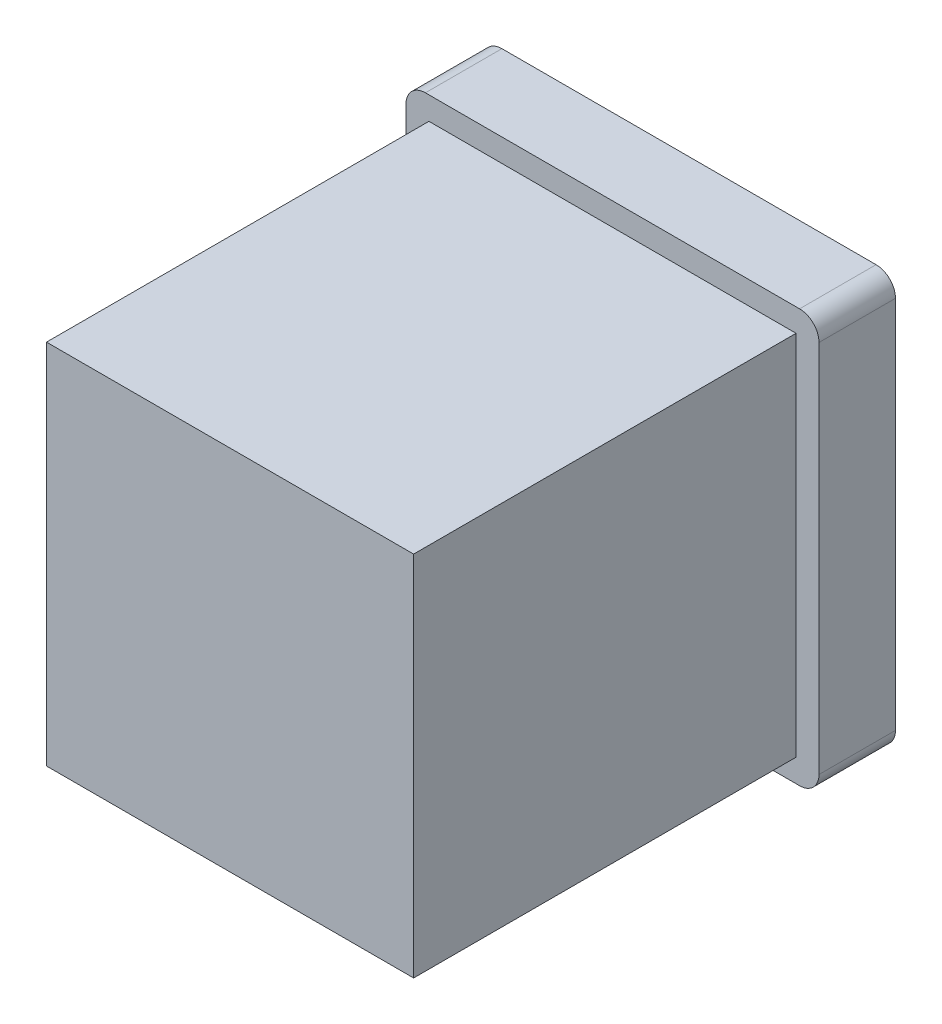
SolidWorks part; units mm, degrees
ref_plane "Front Plane" through (0, 0, 0) normal (0, 0, 1) x (1, 0, 0)
ref_plane "Top Plane" through (0, 0, 0) normal (0, 1, 0) x (1, 0, 0)
ref_plane "Right Plane" through (0, 0, 0) normal (1, 0, 0) x (0, 0, -1)
sketch "Sketch1" plane through (0, 0, 0) normal (0, 0, 1) x (1, 0, 0)
  line L1 (0, 0) -> (27, 0)
  line L2 (0, 0) -> (0, 27)
  line L3 (0, 27) -> (27, 27)
  line L4 (27, 0) -> (27, 27)
  dimension "D1" = 27
  dimension "D2" = 27
extrude "Boss-Extrude1" add sketch "Sketch1" along normal blind 5
sketch "Sketch2" plane through (0, 0, 5) normal (0, 0, 1) x (1, 0, 0)
  line L0 (0, 27) -> (0, 0) construction
  line L1 (1.5, 25.5) -> (25.5, 25.5)
  line L2 (1.5, 25.5) -> (1.5, 1.5)
  line L3 (1.5, 1.5) -> (25.5, 1.5)
  line L4 (25.5, 25.5) -> (25.5, 1.5)
  line L5 (27, 27) -> (0, 27) construction
  point P4 (1.5, 13.5)
  point P7 (0, 13.5)
  point P8 (13.5, 25.5)
  point P11 (13.5, 27)
  dimension "D1" = 0
  dimension "D2" = 0
  dimension "D3" = 24
  dimension "D4" = 24
extrude "Boss-Extrude2" add sketch "Sketch2" along normal blind 25
fillet "Fillet1" radius 1.27 4 edges at (0, 0, 2.5) (27, 0, 2.5) (0, 27, 2.5) (27, 27, 2.5)
sketch "Sketch3" plane through (0, 0, 0) normal (0, 0, -1) x (-1, 0, 0)
  line L0 (-27, 1.27) -> (-27, 25.73) construction
  line L1 (-20.65, 23.19) -> (-18.11, 23.19)
  line L2 (-20.65, 23.19) -> (-20.65, 15.57)
  line L3 (-20.65, 15.57) -> (-18.11, 15.57)
  line L4 (-18.11, 23.19) -> (-18.11, 15.57)
  line L5 (-25.73, 27) -> (-1.27, 27) construction
  line L6 (-8.89, 23.19) -> (-6.35, 23.19)
  line L7 (-8.89, 23.19) -> (-8.89, 15.57)
  line L8 (-8.89, 15.57) -> (-6.35, 15.57)
  line L9 (-6.35, 23.19) -> (-6.35, 15.57)
  line L10 (0, 25.73) -> (0, 1.27) construction
  line L11 (-13.625, 1.4094) -> (-13.625, 7.8295) construction
  line L12 (-16.165, 5.08) -> (-16.165, 8.636)
  line L13 (-11.085, 5.08) -> (-11.085, 8.636)
  line L14 (-16.165, 5.08) -> (-11.085, 5.08)
  line L15 (-1.27, 0) -> (-25.73, 0) construction
  arc A1 (-11.085, 8.636) -> (-16.165, 8.636) centre (-13.625, 7.8295) ccw
  point P16 (-13.5, 5.1417)
  dimension "D10" = 2.665
  dimension "D1" = 2.54
  dimension "D2" = 7.62
  dimension "D3" = 6.35
  dimension "D4" = 2.54
  dimension "D5" = 7.62
  dimension "D6" = 3.81
  dimension "D7" = 6.35
  dimension "D8" = 3.81
  dimension "D9" = 5.08
  dimension "D11" = 3.556
  dimension "D12" = 11.085
  dimension "D13" = 5.08
extrude "Cut-Extrude1" cut sketch "Sketch3" against normal blind 2.54
